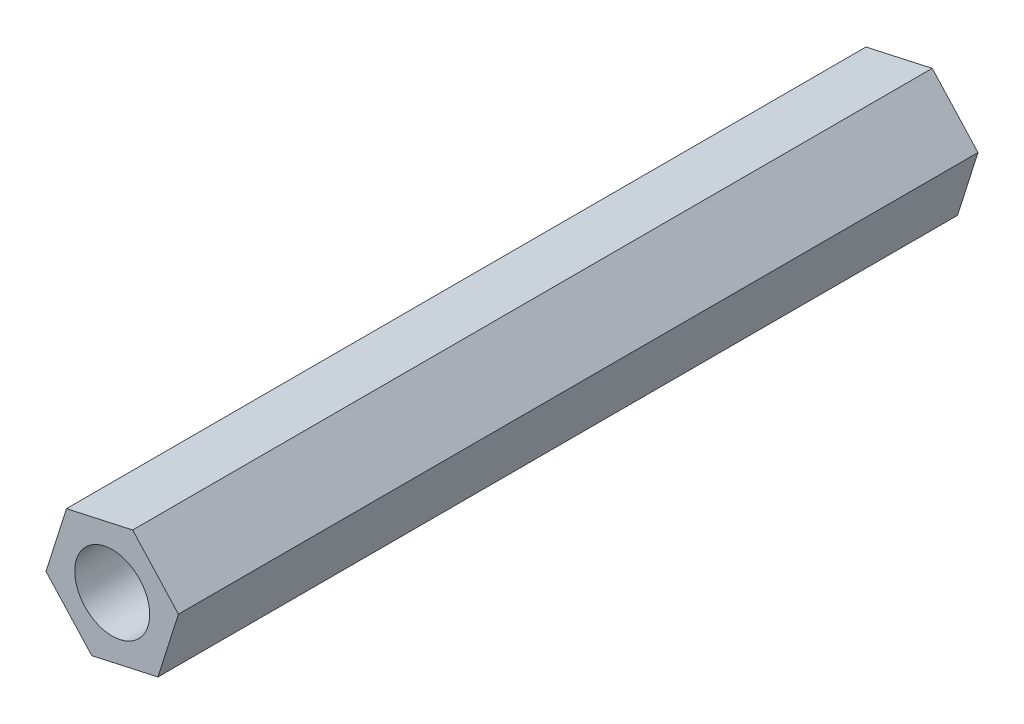
SolidWorks part; units mm, degrees
ref_plane "前视基准面" through (0, 0, 0) normal (0, 0, 1) x (1, 0, 0)
ref_plane "上视基准面" through (0, 0, 0) normal (0, 1, 0) x (1, 0, 0)
ref_plane "右视基准面" through (0, 0, 0) normal (1, 0, 0) x (0, 0, -1)
sketch "草图1" plane through (0, 0, 0) normal (0, 0, 1) x (1, 0, 0)
  line L1 (2.6498, 0.5847) -> (0.8185, 2.5871)
  line L2 (0.8185, 2.5871) -> (-1.8313, 2.0024)
  line L3 (-1.8313, 2.0024) -> (-2.6498, -0.5847)
  line L4 (-2.6498, -0.5847) -> (-0.8185, -2.5871)
  line L5 (-0.8185, -2.5871) -> (1.8313, -2.0024)
  line L6 (1.8313, -2.0024) -> (2.6498, 0.5847)
  circle A0 centre (0, 0) radius 2.35 construction
  circle A1 centre (0, 0) radius 1.5
extrude "凸台-拉伸1" add sketch "草图1" along normal blind 32
